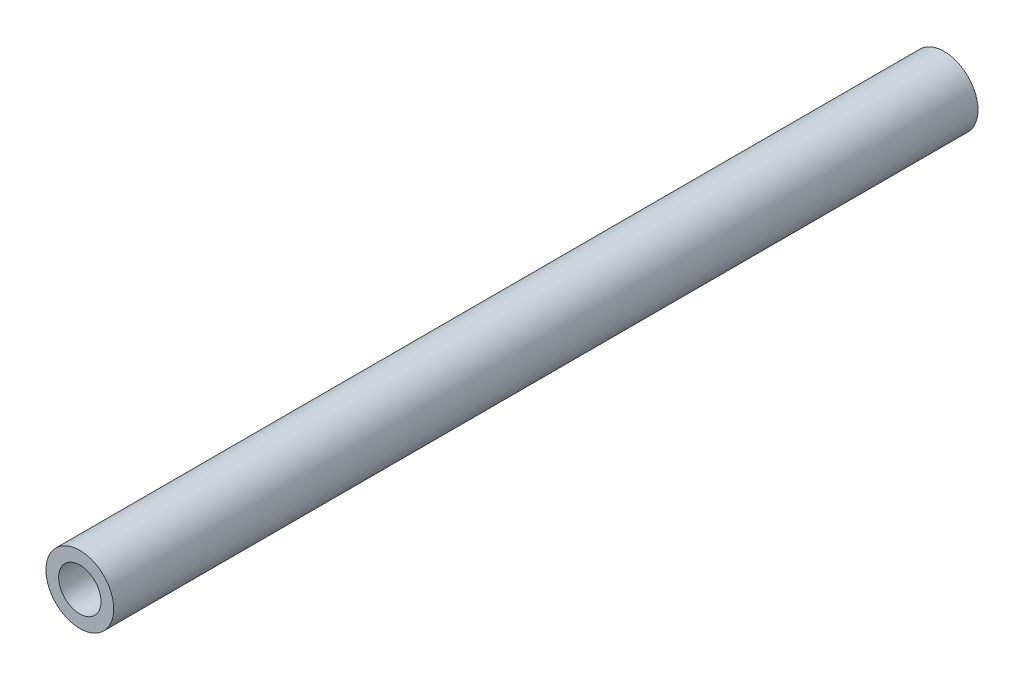
SolidWorks part; units mm, degrees
material "1.0545 (S355N)"
ref_plane "Płaszczyzna przednia" through (0, 0, 0) normal (0, 0, 1) x (1, 0, 0)
ref_plane "Płaszczyzna górna" through (0, 0, 0) normal (0, 1, 0) x (1, 0, 0)
ref_plane "Płaszczyzna prawa" through (0, 0, 0) normal (1, 0, 0) x (0, 0, -1)
sketch "Szkic1" plane through (0, 0, 0) normal (0, 0, 1) x (1, 0, 0)
  circle A0 centre (0, 0) radius 8
  circle A1 centre (0, 0) radius 4
  dimension "D1" = 16
  dimension "D2" = 4
extrude "Dodanie-wyciągnięcie1" add sketch "Szkic1" along normal mid plane 204
sketch "Szkic2" plane through (0, 0, 102) normal (0, 0, 1) x (1, 0, 0)
  circle A0 centre (0, 0) radius 5
  circle A2 centre (0, 0) radius 4 construction
  dimension "D1" = 1
extrude "Wytnij-wyciągnięcie1" cut sketch "Szkic2" against normal blind 40
sketch "Szkic3" plane through (0, 0, -102) normal (0, 0, -1) x (-1, 0, 0)
  circle A0 centre (0, 0) radius 5
  circle A1 centre (0, 0) radius 4 construction
  dimension "D1" = 1
extrude "Wytnij-wyciągnięcie2" cut sketch "Szkic3" against normal blind 30
